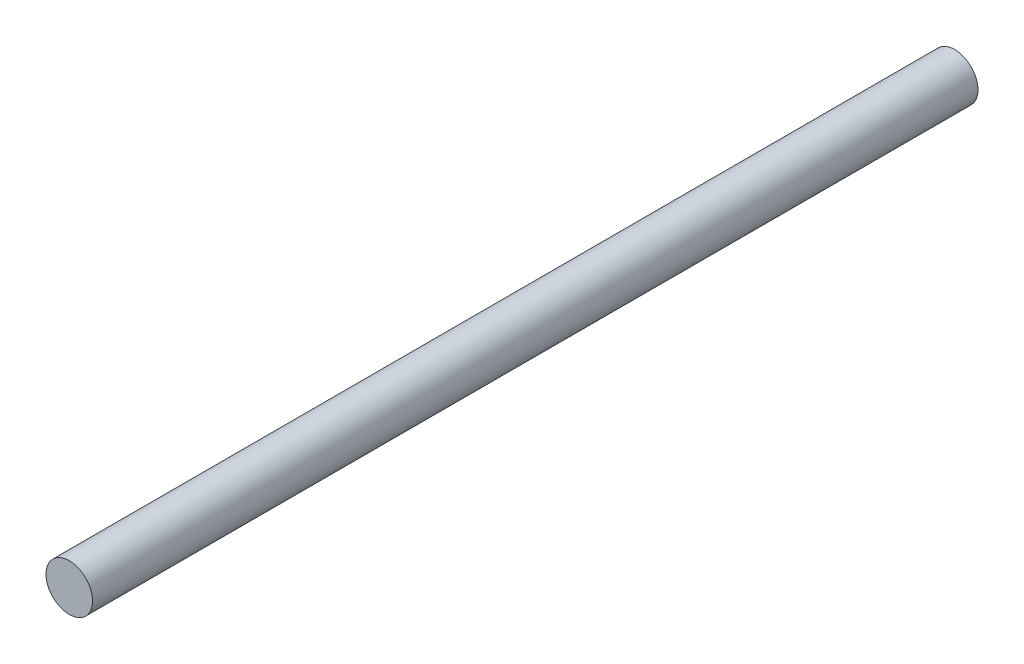
SolidWorks part; units mm, degrees
ref_plane "Front Plane" through (0, 0, 0) normal (0, 0, 1) x (1, 0, 0)
ref_plane "Top Plane" through (0, 0, 0) normal (0, 1, 0) x (1, 0, 0)
ref_plane "Right Plane" through (0, 0, 0) normal (1, 0, 0) x (0, 0, -1)
sketch "Sketch1" plane through (0, 0, 0) normal (0, 0, 1) x (1, 0, 0)
  circle A0 centre (0, 0) radius 2
  dimension "D1" = 4
extrude "Boss-Extrude1" add sketch "Sketch1" along normal blind 76
